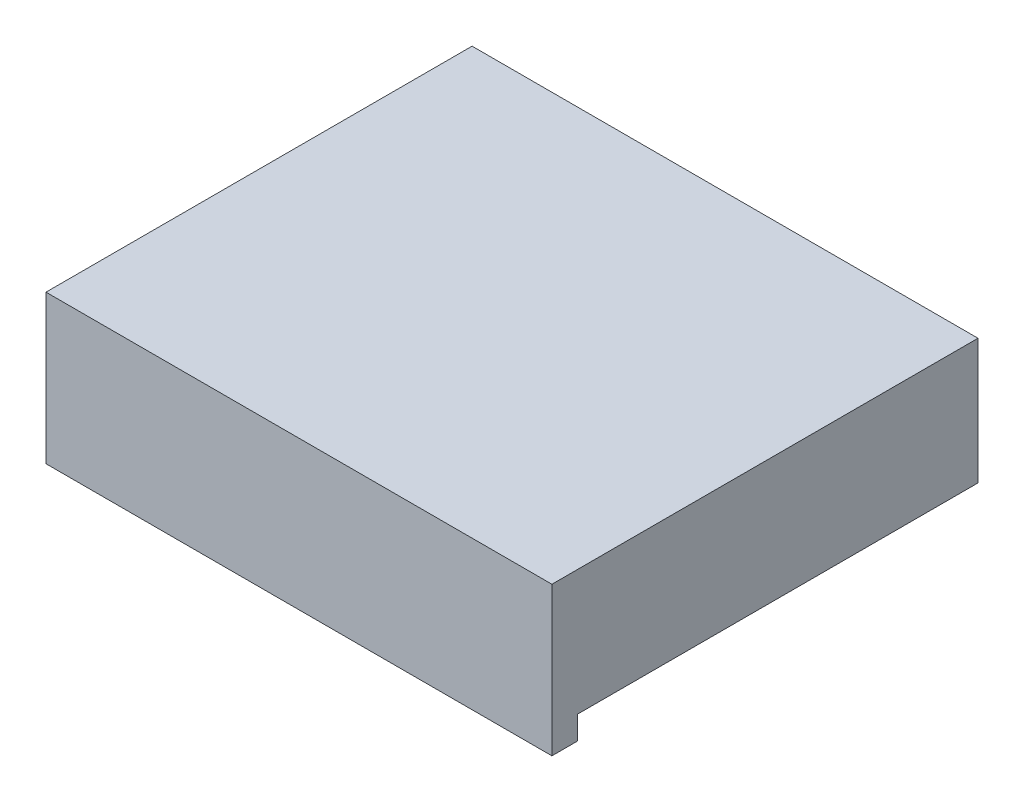
SolidWorks part; units mm, degrees
ref_plane "Alzado" through (0, 0, 0) normal (0, 0, 1) x (1, 0, 0)
ref_plane "Planta" through (0, 0, 0) normal (0, 1, 0) x (1, 0, 0)
ref_plane "Vista lateral" through (0, 0, 0) normal (1, 0, 0) x (0, 0, -1)
sketch "Croquis1" plane through (0, 0, 0) normal (1, 0, 0) x (0, 0, -1)
  line L1 (0, 0) -> (-86.3, 0)
  line L2 (0, 0) -> (0, 27)
  line L3 (0, 27) -> (-91.8, 27)
  line L5 (-91.8, -5.021) -> (-86.3, -5.021)
  line L6 (-86.3, -5.021) -> (-86.3, 0)
  line L7 (-91.8, -5.021) -> (-91.8, 27)
  dimension "D1" = 27
  dimension "D2" = 5.5
  dimension "D3" = 91.8
extrude "Saliente-Extruir1" add sketch "Croquis1" along normal blind 109
